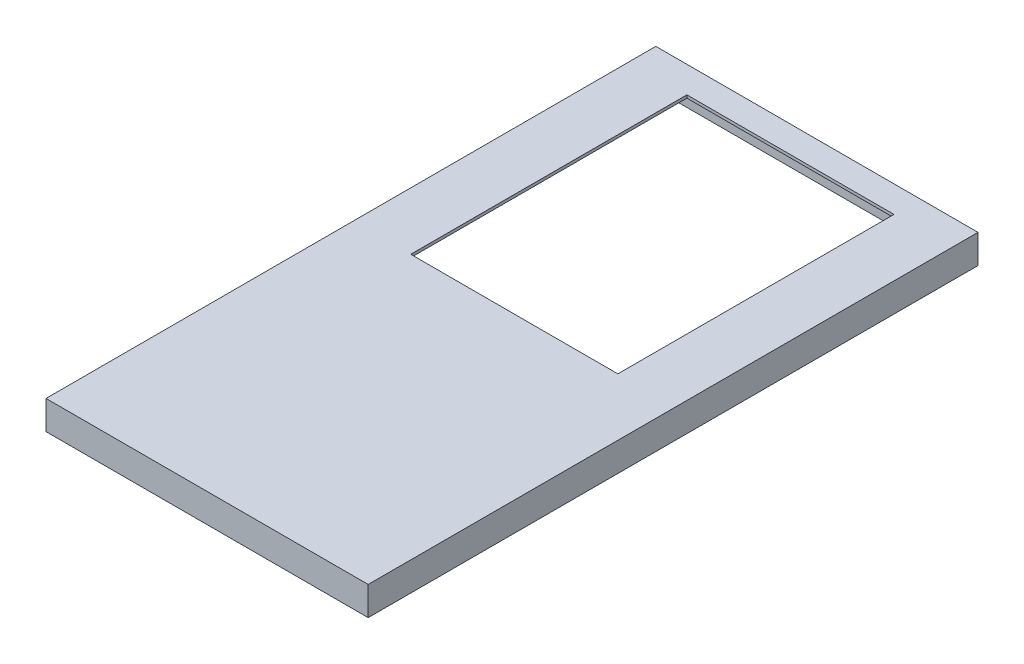
SolidWorks part; units mm, degrees
ref_plane "Front Plane" through (0, 0, 0) normal (0, 0, 1) x (1, 0, 0)
ref_plane "Top Plane" through (0, 0, 0) normal (0, 1, 0) x (1, 0, 0)
ref_plane "Right Plane" through (0, 0, 0) normal (1, 0, 0) x (0, 0, -1)
sketch "Sketch1" plane through (0, 0, 0) normal (0, 1, 0) x (1, 0, 0)
  line L1 (-28, -53) -> (28, -53)
  line L2 (-28, -53) -> (-28, 53)
  line L3 (-28, 53) -> (28, 53)
  line L4 (28, -53) -> (28, 53)
  line L5 (-28, -53) -> (28, 53) construction
  line L6 (-28, 53) -> (28, -53) construction
  point P0 (0, 0)
  dimension "D1" = 106
  dimension "D2" = 56
extrude "Boss-Extrude1" add sketch "Sketch1" against normal blind 5
shell "Shell1" thickness 1.5
sketch "Sketch2" plane through (0, 0, 0) normal (0, 1, 0) x (1, 0, 0)
  line L0 (-28, 53) -> (-28, -53) construction
  line L1 (-18, 48.4) -> (18, 48.4)
  line L2 (-18, 48.4) -> (-18, 0.4)
  line L3 (-18, 0.4) -> (18, 0.4)
  line L4 (18, 48.4) -> (18, 0.4)
  line L5 (-18, 48.4) -> (18, 0.4) construction
  line L6 (-18, 0.4) -> (18, 48.4) construction
  line L8 (26.5, 51.5) -> (-26.5, 51.5) construction
  point P0 (0, 24.4)
  point P5 (0, 48.4)
  dimension "D1" = 48
  dimension "D2" = 36
  dimension "D3" = 10
  dimension "D4" = 3.1
extrude "Cut-Extrude1" cut sketch "Sketch2" against normal through all
sketch "Sketch3" plane through (0, -0.5, 0) normal (0, -1, 0) x (1, 0, 0)
  line L5 (18, -48.4) -> (-18, -48.4) construction
  line L6 (-21.6, -51.5) -> (21.6, -51.5)
  line L7 (-21.6, -51.5) -> (-21.6, 9.2)
  line L8 (-21.6, 9.2) -> (-18.1, 9.2)
  line L13 (21.6, -51.5) -> (21.6, 9.2)
  line L14 (-21.6, -51.5) -> (21.6, 9.2) construction
  line L16 (-21.6, 9.2) -> (21.6, -51.5) construction
  line L17 (-23.1, -53) -> (23.1, -53)
  line L18 (23.1, -53) -> (23.1, 10.7)
  line L19 (-23.1, 10.7) -> (-18.1, 10.7)
  line L20 (-23.1, -53) -> (-23.1, 10.7)
  line L21 (-18.1, 9.2) -> (-18.1, 10.7)
  line L22 (18.1, 10.7) -> (18.1, 9.2)
  line L23 (18.1, 10.7) -> (23.1, 10.7)
  line L24 (-23.1, 10.7) -> (23.1, 10.7) construction
  line L25 (18.1, 9.2) -> (21.6, 9.2)
  line L26 (-21.6, 9.2) -> (21.6, 9.2) construction
  point P0 (0, -21.15)
  dimension "D1" = 60.7
  dimension "D2" = 43.2
  dimension "D3" = 3.1
  dimension "D4" = 1.5
  dimension "D5" = 5
  dimension "D6" = 5
extrude "Boss-Extrude2" add sketch "Sketch3" along normal blind 2.3
sketch "Sketch4" plane through (0, -0.5, 0) normal (0, -1, 0) x (1, 0, 0)
  line L0 (28, -53) -> (-28, -53) construction
  line L1 (28, 53) -> (28, -53) construction
  circle A0 centre (25.25, -50.25) radius 2.75
  point P8 (25.25, -50.25)
  dimension "D1" = 5.5
extrude "Boss-Extrude3" add sketch "Sketch4" along normal blind 4.5
sketch "Sketch5" plane through (0, -5, 0) normal (0, -1, 0) x (1, 0, 0)
  circle A0 centre (25.25, -50.25) radius 1.8
  dimension "D1" = 3.6
extrude "Cut-Extrude2" cut sketch "Sketch5" against normal blind 4.5
mirror "Mirror1" about plane through (0, 0, 0) normal (0, 0, 1) of "Cut-Extrude2", "Boss-Extrude3"
mirror "Mirror2" about plane through (0, 0, 0) normal (1, 0, 0) of "Mirror1", "Boss-Extrude3", "Cut-Extrude2"
